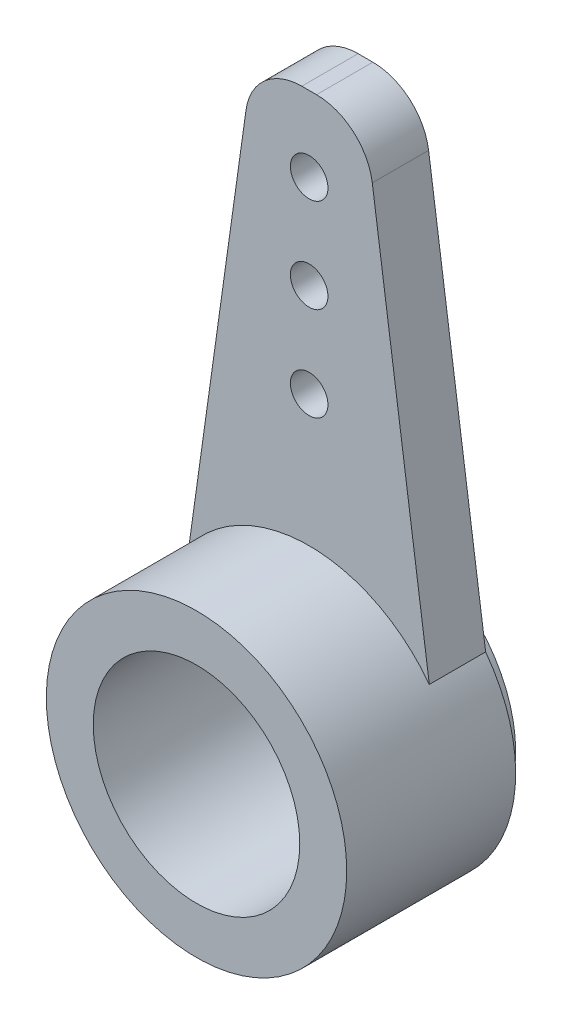
SolidWorks part; units mm, degrees
ref_plane "Front" through (0, 0, 0) normal (0, 0, 1) x (1, 0, 0)
ref_plane "Top" through (0, 0, 0) normal (0, 1, 0) x (1, 0, 0)
ref_plane "Right" through (0, 0, 0) normal (1, 0, 0) x (0, 0, -1)
sketch "Sketch1" plane through (0, 0, 0) normal (0, 0, 1) x (1, 0, 0)
  line L0 (0, 0) -> (0, 33.5454) construction
  line L1 (-0.196, 14.5) -> (0.196, 14.5) construction
  line L2 (-3.2, 2.4) -> (-1.6814, 13.2087)
  line L3 (3.2, 2.4) -> (1.6814, 13.2087)
  line L4 (-0.196, 14.5) -> (0.196, 14.5)
  arc A0 (-3.2, 2.4) -> (3.2, 2.4) centre (0, 0) ccw
  circle A1 centre (0, 10) radius 0.5
  circle A2 centre (0, 12.5) radius 0.5
  circle A3 centre (0, 7.5) radius 0.5
  arc A4 (1.6814, 13.2087) -> (0.196, 14.5) centre (0.196, 13) ccw
  arc A5 (-0.196, 14.5) -> (-1.6814, 13.2087) centre (-0.196, 13) ccw
  circle A6 centre (0, 0) radius 1.5
  dimension "D1" = 8
  dimension "D3" = 1
  dimension "D5" = 1
  dimension "D6" = 1
  dimension "D11" = 1.5
  dimension "D9" = 1.5
  dimension "D12" = 3
  dimension "D2" = 14.5
  dimension "D4" = 10
  dimension "D7" = 2.5
  dimension "D8" = 2.5
  dimension "D10" = 3.2
extrude "Boss-Extrude3" add sketch "Sketch1" along normal blind 1.5
sketch "Sketch2" plane through (0, 0, 1.5) normal (0, 0, 1) x (1, 0, 0)
  circle A0 centre (0, 0) radius 4
extrude "Boss-Extrude4" add sketch "Sketch2" along normal blind 3
sketch "Sketch3" plane through (0, 0, 0) normal (0, 0, -1) x (-1, 0, 0)
  circle A0 centre (0, 0) radius 3.5
  circle A4 centre (0, 0) radius 3.25
  dimension "D1" = 7
  dimension "D2" = 0.25
extrude "Boss-Extrude5" add sketch "Sketch3" along normal blind 0.5
sketch "Sketch4" plane through (0, 0, 4.5) normal (0, 0, 1) x (1, 0, 0)
  circle A0 centre (0, 0) radius 2.75
  dimension "D1" = 5.5
extrude "Cut-Extrude1" cut sketch "Sketch4" against normal blind 4
